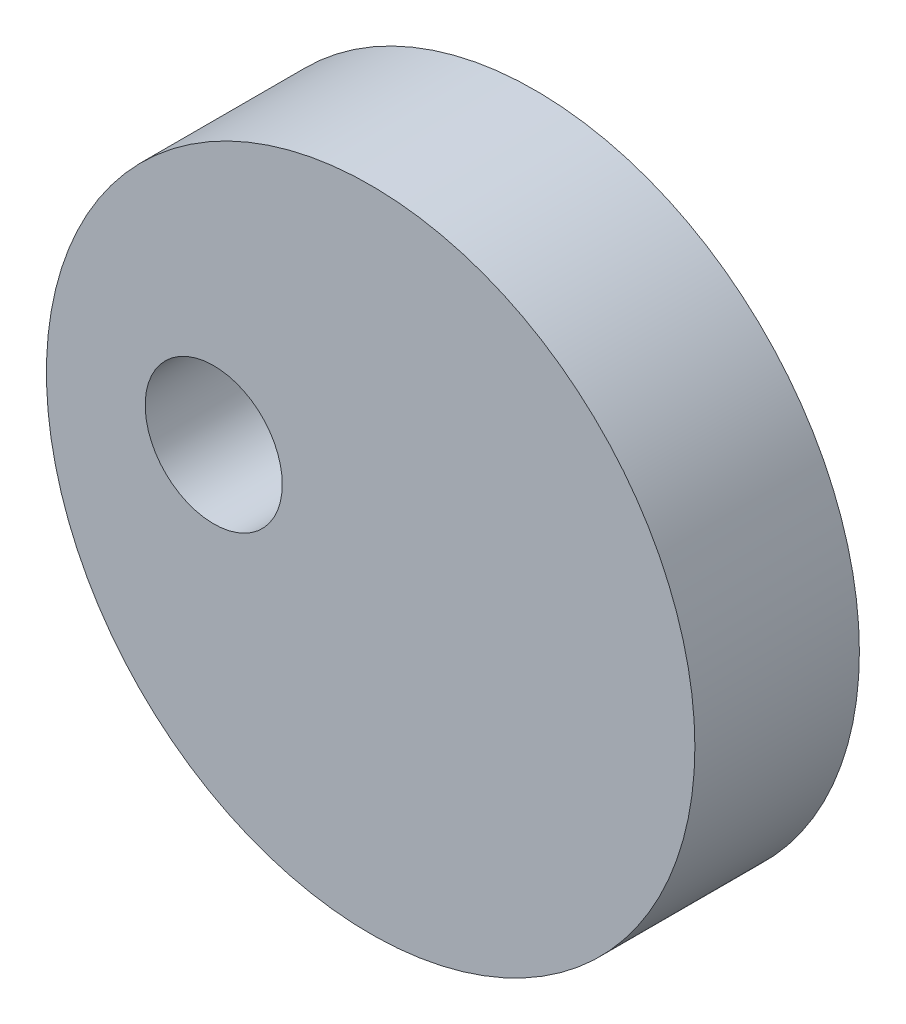
SolidWorks part; units mm, degrees
ref_plane "Front Plane" through (0, 0, 0) normal (0, 0, 1) x (1, 0, 0)
ref_plane "Top Plane" through (0, 0, 0) normal (0, 1, 0) x (1, 0, 0)
ref_plane "Right Plane" through (0, 0, 0) normal (1, 0, 0) x (0, 0, -1)
sketch "Sketch1" plane through (0, 0, 0) normal (0, 0, 1) x (1, 0, 0)
  circle A0 centre (0, 0) radius 59.1298
extrude "Boss-Extrude1" add sketch "Sketch1" along normal blind 30
sketch "Sketch4" plane through (0, 0, 30) normal (0, 0, 1) x (1, 0, 0)
  point P0 (-28.6215, 3.82)
hole_wizard "Ø25.0mm Dowel Hole1" positions "Sketch4" profile "Sketch3" hole size "Ø25.0" standard "DIN" end condition through all
sketch "Sketch3" plane through (-28.6215, 3.82, 30) normal (1, 0, 0) x (0, -1, 0)
  line L0 (0, 0) -> (0, 30)
  line L1 (0, 30) -> (12.5, 30)
  line L2 (12.5, 30) -> (12.5, 0)
  line L5 (12.5, 0) -> (0, 0)
  line L11 (0, -6.35) -> (0, 107.95) construction
  dimension "Thru Hole Dia." = 25
  dimension "Thru Hole Depth" = 30
